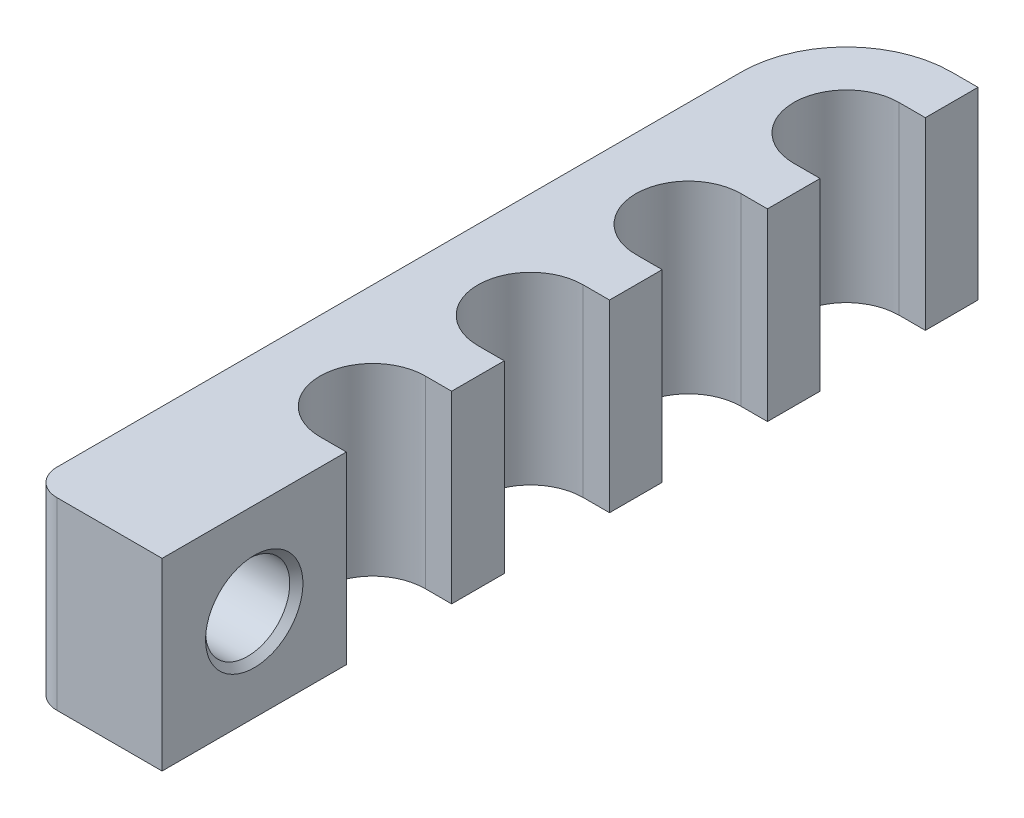
SolidWorks part; units mm, degrees
material "ABS"
ref_plane "Front Plane" through (0, 0, 0) normal (0, 0, 1) x (1, 0, 0)
ref_plane "Top Plane" through (0, 0, 0) normal (0, 1, 0) x (1, 0, 0)
ref_plane "Right Plane" through (0, 0, 0) normal (1, 0, 0) x (0, 0, -1)
sketch "Sketch1" plane through (0, 0, 0) normal (0, 1, 0) x (1, 0, 0)
  line L0 (0, 0) -> (-5, 0)
  line L1 (-5, 0) -> (-5, 9.0655)
  line L2 (0, 13) -> (0, 11)
  line L3 (0, 0) -> (0, 7)
  line L4 (0, 2) -> (-5, 2) construction
  line L5 (0, 5) -> (-5, 5) construction
  line L6 (-5, 7) -> (-8, 7) construction
  line L7 (-8, 7) -> (-8, 0) construction
  line L8 (-8, 0) -> (-5, 0) construction
  line L9 (-2.5, 5) -> (-2.5, 2) construction
  line L10 (0, 11) -> (-1, 11)
  line L11 (-1, 7) -> (0, 7)
  line L13 (0, 3.5) -> (-5, 3.5) construction
  line L14 (0, 13) -> (-1, 13)
  line L15 (-1, 17) -> (0, 17)
  line L16 (0, 17) -> (0, 19)
  line L18 (-5, 27) -> (-5, 9.0655)
  line L19 (0, 19) -> (-1, 19)
  line L20 (-1, 23) -> (0, 23)
  line L21 (0, 23) -> (0, 25)
  line L22 (0, 25) -> (-1, 25)
  line L23 (-1, 29) -> (0, 29)
  line L24 (0, 29) -> (0, 31)
  line L25 (0, 31) -> (-1, 31)
  arc A2 (-1, 11) -> (-1, 7) centre (-1, 9) ccw
  arc A4 (-1, 13) -> (-1, 17) centre (-1, 15) cw
  arc A6 (-1, 19) -> (-1, 23) centre (-1, 21) cw
  arc A7 (-1, 25) -> (-1, 29) centre (-1, 27) cw
  arc A8 (-1, 31) -> (-5, 27) centre (-1, 27) ccw
  point P19 (-8, 3.5)
  point P20 (-2.5, 3.5)
  point P28 (-2.5, 3.5)
  point P32 (-2.1302, 21)
  point P44 (-4.9413, 24.9053)
  dimension "D1" = 2
  dimension "D2" = 2
  dimension "D3" = 3
  dimension "D4" = 7
  dimension "D5" = 3
  dimension "D6" = 1
  dimension "D7" = 3.5
  dimension "D8" = 3.5
extrude "Boss-Extrude1" add sketch "Sketch1" along normal blind 7
hole_wizard "M3 Clearance Hole1" positions "Sketch2" profile "Sketch3" hole size "M3" standard "ANSI Metric" end condition up to next
sketch "Sketch2" plane through (-5, 0, 0) normal (-1, 0, 0) x (0, 0, 1)
  line L0 (0, 0) -> (-7, 7) construction
  line L1 (-27, 7) -> (0, 7) construction
  line L2 (-7, 7) -> (0, 7) construction
  line L3 (0, 7) -> (0, 0) construction
  point P0 (-3.5, 3.5)
sketch "Sketch3" plane through (-5, 3.5, -3.5) normal (0, 1, 0) x (0, 0, 1)
  line L0 (0, 0) -> (0, 5)
  line L1 (0, 5) -> (1.6, 5)
  line L2 (1.6, 5) -> (1.6, 0)
  line L5 (1.6, 0) -> (0, 0)
  line L11 (0, -6.35) -> (0, 107.95) construction
  dimension "Thru Hole Dia." = 3.2
  dimension "Thru Hole Depth" = 5
chamfer "Chamfer2" distance 0.25 angle 45 2 edges at (-5, 3.5, -1.9) (0, 3.5, -1.9)
fillet "Fillet1" radius 1 1 edges at (-5, 3.5, 0)
